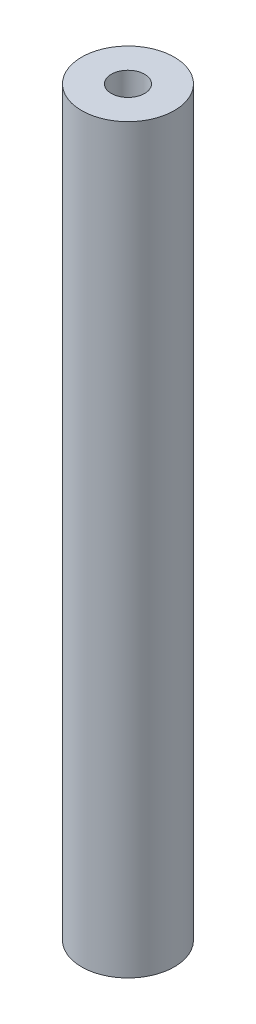
SolidWorks part; units mm, degrees
ref_plane "Front Plane" through (0, 0, 0) normal (0, 0, 1) x (1, 0, 0)
ref_plane "Top Plane" through (0, 0, 0) normal (0, 1, 0) x (1, 0, 0)
ref_plane "Right Plane" through (0, 0, 0) normal (1, 0, 0) x (0, 0, -1)
sketch "Sketch1" plane through (0, 0, 0) normal (0, 1, 0) x (1, 0, 0)
  circle A0 centre (0, 0) radius 5.5562
  dimension "D1" = 11.1125
extrude "Boss-Extrude1" add sketch "Sketch1" along normal blind 88.9
sketch "Sketch2" plane through (0, 88.9, 0) normal (0, 1, 0) x (1, 0, 0)
  circle A0 centre (0, 0) radius 2
  dimension "D1" = 4
extrude "Cut-Extrude1" cut sketch "Sketch2" against normal blind 7
sketch "Sketch3" plane through (0, 0, 0) normal (0, -1, 0) x (1, 0, 0)
  circle A0 centre (0, 0) radius 2
  dimension "D1" = 4
extrude "Cut-Extrude2" cut sketch "Sketch3" against normal blind 7
